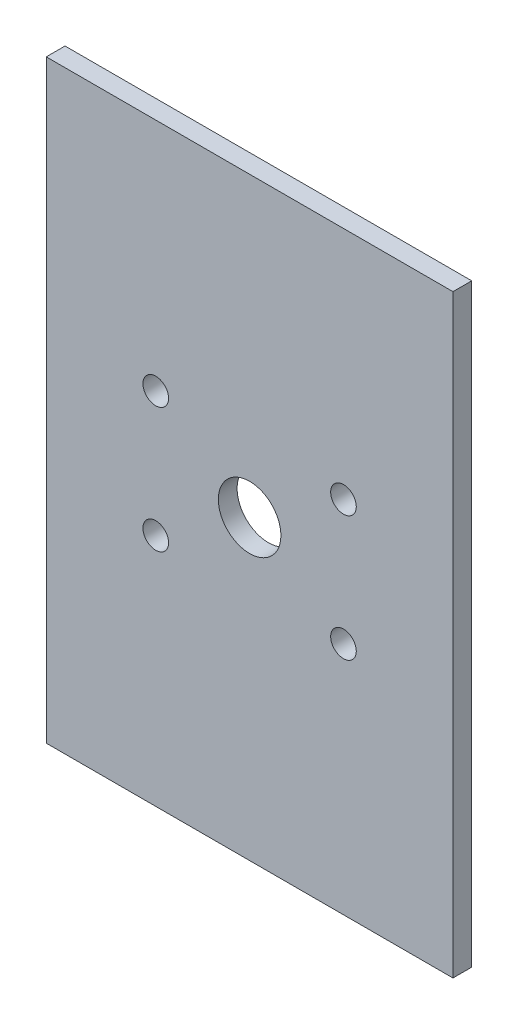
SolidWorks part; units mm, degrees
ref_plane "Front Plane" through (0, 0, 0) normal (0, 0, 1) x (1, 0, 0)
ref_plane "Top Plane" through (0, 0, 0) normal (0, 1, 0) x (1, 0, 0)
ref_plane "Right Plane" through (0, 0, 0) normal (1, 0, 0) x (0, 0, -1)
sketch "Sketch1" plane through (0, 0, 0) normal (0, 0, 1) x (1, 0, 0)
  line L1 (-65, 95) -> (65, 95)
  line L2 (-65, 95) -> (-65, -95)
  line L3 (-65, -95) -> (65, -95)
  line L4 (65, 95) -> (65, -95)
  line L5 (-65, 95) -> (65, -95) construction
  line L6 (-65, -95) -> (65, 95) construction
  point P0 (0, 0)
  dimension "D1" = 130
  dimension "D2" = 190
extrude "Boss-Extrude1" add sketch "Sketch1" along normal blind 6
sketch "Sketch2" plane through (0, 0, 6) normal (0, 0, 1) x (1, 0, 0)
  line L0 (0, 95) -> (0, -95) construction
  line L1 (65, 95) -> (-65, 95) construction
  line L2 (-65, -95) -> (65, -95) construction
  line L3 (-65, 0) -> (65, 0) construction
  line L4 (-65, 95) -> (-65, -95) construction
  line L5 (65, -95) -> (65, 95) construction
  circle A14 centre (0, 0) radius 10
  dimension "D1" = 20
sketch "Sketch3" plane through (0, 0, 6) normal (0, 0, 1) x (1, 0, 0)
  line L0 (0, 95) -> (0, -95) construction
  line L1 (65, 95) -> (-65, 95) construction
  line L2 (-65, -95) -> (65, -95) construction
  line L3 (-65, 0) -> (65, 0) construction
  line L4 (-65, 95) -> (-65, -95) construction
  line L5 (65, -95) -> (65, 95) construction
  line L7 (-30, 20) -> (30, 20) construction
  line L8 (-30, 20) -> (-30, -20) construction
  line L9 (-30, -20) -> (30, -20) construction
  line L10 (30, 20) -> (30, -20) construction
  line L11 (-30, 20) -> (30, -20) construction
  line L12 (-30, -20) -> (30, 20) construction
  point P12 (0, 0)
  dimension "D1" = 60
  dimension "D2" = 40
extrude "Cut-Extrude1" cut sketch "Sketch2" against normal up to next
hole_wizard "M8 Clearance Hole1" positions "3DSketch1" profile "Sketch4" hole size "M8" standard "ANSI Metric"
sketch3d "3DSketch1"
  point P0 (-30, 20, 6)
  point P3 (30, 20, 6)
  point P6 (30, -20, 6)
  point P9 (-30, -20, 6)
sketch "Sketch4" plane through (-30, 20, 6) normal (1, 0, 0) x (0, -1, 0)
  line L0 (0, 0) -> (0, 22.2135)
  line L1 (0, 22.2135) -> (4.1, 19.75)
  line L2 (4.1, 19.75) -> (4.1, 0)
  line L5 (4.1, 0) -> (0, 0)
  line L10 (0, 22.2135) -> (-4.1, 19.75) construction
  line L11 (0, -6.35) -> (0, 107.95) construction
  dimension "Hole Dia." = 8.2
  dimension "Hole Depth" = 19.75
  dimension "Drill Angle" = 118
